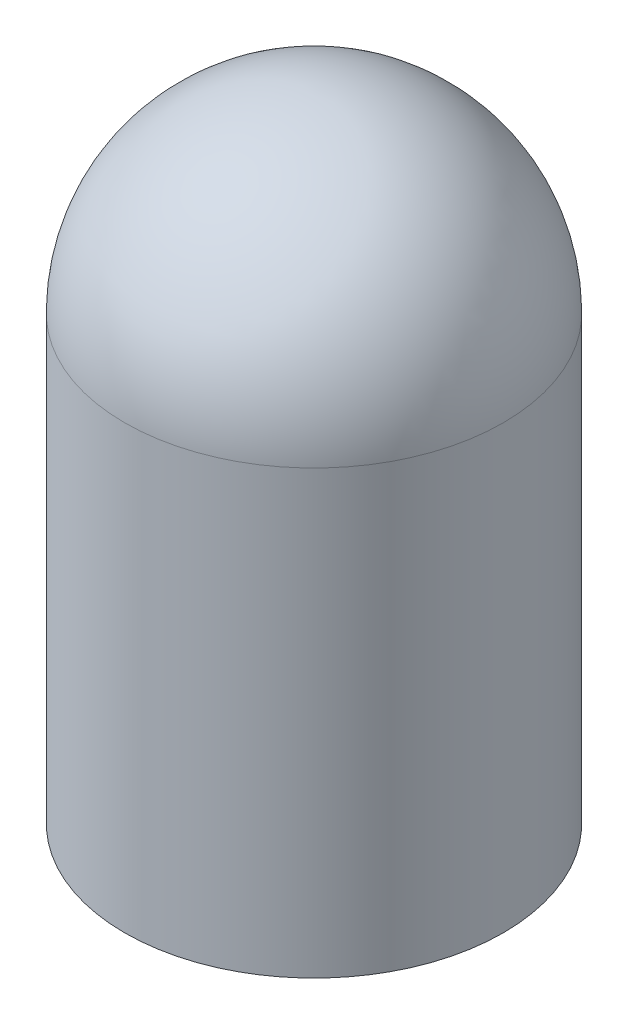
SolidWorks part; units mm, degrees
ref_plane "Front Plane" through (0, 0, 0) normal (0, 0, 1) x (1, 0, 0)
ref_plane "Top Plane" through (0, 0, 0) normal (0, 1, 0) x (1, 0, 0)
ref_plane "Right Plane" through (0, 0, 0) normal (1, 0, 0) x (0, 0, -1)
sketch "Sketch1" plane through (0, 0, 0) normal (0, 0, 1) x (1, 0, 0)
  line L0 (0, 0) -> (60, 0)
  line L1 (60, 0) -> (60, 140)
  line L2 (0, 200) -> (0, 0)
  arc A0 (60, 140) -> (0, 200) centre (0, 140) ccw
  dimension "D2" = 60
  dimension "D1" = 60
  dimension "D3" = 200
revolve "Revolve2" add sketch "Sketch1" angle 360 about L2
shell "Shell3" thickness 2
